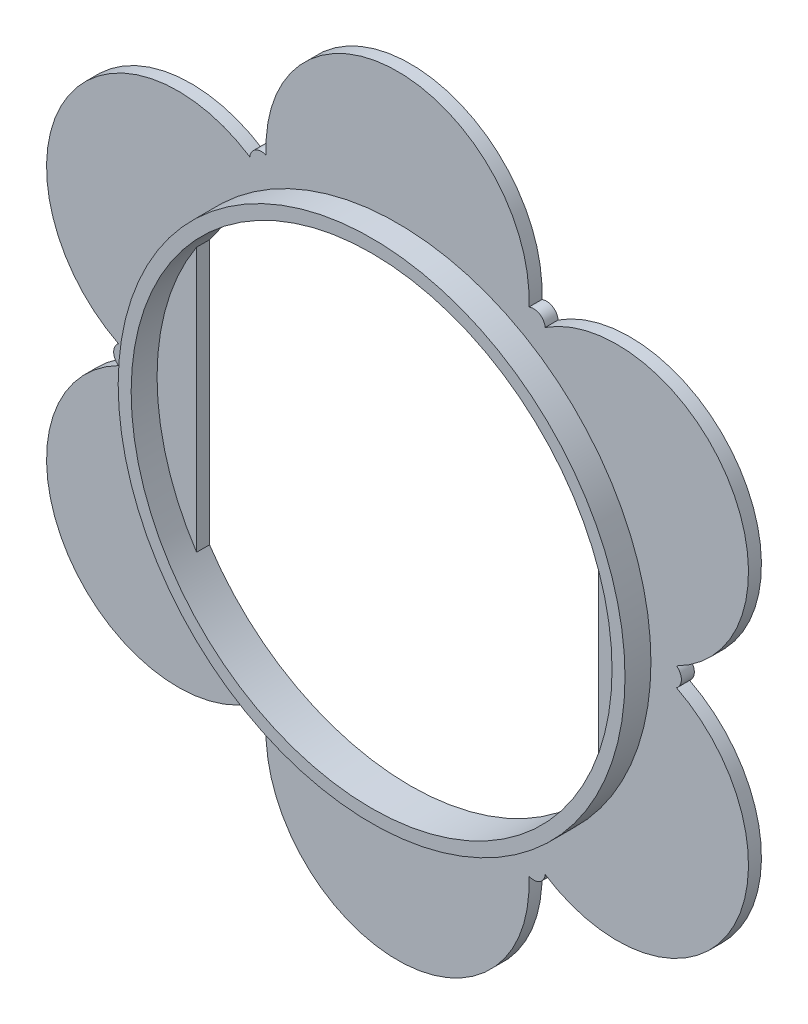
SolidWorks part; units mm, degrees
ref_plane "Front Plane" through (0, 0, 0) normal (0, 0, 1) x (1, 0, 0)
ref_plane "Top Plane" through (0, 0, 0) normal (0, 1, 0) x (1, 0, 0)
ref_plane "Right Plane" through (0, 0, 0) normal (1, 0, 0) x (0, 0, -1)
ref_plane "Plane1" through (0, 0, 1.8691) normal (0, 0, 1) x (1, 0, 0)
sketch "Sketch2" plane through (0, 0, 1.8691) normal (0, 0, 1) x (1, 0, 0)
  line L0 (-31, 20.3816) -> (-31, -20.3816)
  line L1 (0, -59.0896) -> (0, 59.3896) construction
  line L2 (31, 20.3816) -> (31, -20.3816)
  line L3 (0, 0) -> (0, 66.0605) construction
  circle A1 centre (-20.9977, 36.3691) radius 2 construction
  arc A3 (-20.474, -38.2993) -> (20.474, -38.2993) centre (0, -39.1) ccw construction
  arc A5 (-20.474, 38.2993) -> (-22.9311, 36.8806) centre (-20.9977, 36.3691) ccw construction
  arc A7 (20.474, 38.2993) -> (-20.474, 38.2993) centre (0, 39.1) ccw construction
  arc A9 (20.474, 38.2993) -> (-20.474, 38.2993) centre (0, 39.1) ccw construction
  arc A11 (-22.9311, 36.8806) -> (-43.4051, 1.4186) centre (-33.8616, 19.55) ccw construction
  arc A13 (-22.9311, 36.8806) -> (-43.4051, 1.4186) centre (-33.8616, 19.55) ccw construction
  arc A15 (21.4752, 38.3112) -> (20.474, 38.2993) centre (20.9977, 36.3691) ccw construction
  arc A17 (21.4752, 38.3112) -> (20.474, 38.2993) centre (20.9977, 36.3691) ccw construction
  arc A23 (22.4409, 37.7537) -> (21.4752, 38.3112) centre (20.9977, 36.3691) ccw construction
  arc A25 (22.4409, 37.7537) -> (21.4752, 38.3112) centre (20.9977, 36.3691) ccw construction
  arc A27 (-20.474, -38.2993) -> (20.474, -38.2993) centre (0, -39.1) ccw construction
  arc A28 (43.4051, 1.4186) -> (22.9311, 36.8806) centre (33.8616, 19.55) ccw construction
  arc A29 (43.4051, 1.4186) -> (22.9311, 36.8806) centre (33.8616, 19.55) ccw construction
  arc A30 (22.9311, 36.8806) -> (22.4409, 37.7537) centre (20.9977, 36.3691) ccw construction
  arc A31 (22.9311, 36.8806) -> (22.4409, 37.7537) centre (20.9977, 36.3691) ccw construction
  arc A32 (43.9161, 0.5576) -> (43.4051, 1.4186) centre (41.9954, 0) ccw construction
  arc A33 (43.9161, 0.5576) -> (43.4051, 1.4186) centre (41.9954, 0) ccw construction
  arc A34 (20.474, -38.2993) -> (21.4752, -38.3112) centre (20.9977, -36.3691) ccw construction
  arc A35 (22.9311, -36.8806) -> (43.4051, -1.4186) centre (33.8616, -19.55) ccw construction
  arc A36 (22.9311, -36.8806) -> (43.4051, -1.4186) centre (33.8616, -19.55) ccw construction
  arc A37 (43.4051, -1.4186) -> (43.9161, -0.5576) centre (41.9954, 0) ccw construction
  arc A38 (43.4051, -1.4186) -> (43.9161, -0.5576) centre (41.9954, 0) ccw construction
  arc A39 (43.9161, -0.5576) -> (43.9161, 0.5576) centre (41.9954, 0) ccw construction
  arc A40 (43.9161, -0.5576) -> (43.9161, 0.5576) centre (41.9954, 0) ccw construction
  arc A41 (20.474, -38.2993) -> (21.4752, -38.3112) centre (20.9977, -36.3691) ccw construction
  arc A42 (21.4752, -38.3112) -> (22.4409, -37.7537) centre (20.9977, -36.3691) ccw construction
  arc A43 (21.4752, -38.3112) -> (22.4409, -37.7537) centre (20.9977, -36.3691) ccw construction
  arc A44 (22.4409, -37.7537) -> (22.9311, -36.8806) centre (20.9977, -36.3691) ccw construction
  arc A45 (22.4409, -37.7537) -> (22.9311, -36.8806) centre (20.9977, -36.3691) ccw construction
  arc A46 (-21.4752, -38.3112) -> (-20.474, -38.2993) centre (-20.9977, -36.3691) ccw construction
  arc A47 (-21.4752, -38.3112) -> (-20.474, -38.2993) centre (-20.9977, -36.3691) ccw construction
  arc A48 (-22.4409, -37.7537) -> (-21.4752, -38.3112) centre (-20.9977, -36.3691) ccw construction
  arc A49 (-22.4409, -37.7537) -> (-21.4752, -38.3112) centre (-20.9977, -36.3691) ccw construction
  arc A50 (-22.9311, -36.8806) -> (-22.4409, -37.7537) centre (-20.9977, -36.3691) ccw construction
  arc A51 (-22.9311, -36.8806) -> (-22.4409, -37.7537) centre (-20.9977, -36.3691) ccw construction
  arc A52 (-43.4051, -1.4186) -> (-22.9311, -36.8806) centre (-33.8616, -19.55) ccw construction
  arc A53 (-43.4051, -1.4186) -> (-22.9311, -36.8806) centre (-33.8616, -19.55) ccw construction
  arc A54 (-43.9161, -0.5576) -> (-43.4051, -1.4186) centre (-41.9954, 0) ccw construction
  arc A55 (-43.9161, -0.5576) -> (-43.4051, -1.4186) centre (-41.9954, 0) ccw construction
  arc A56 (-43.9161, 0.5576) -> (-43.9161, -0.5576) centre (-41.9954, 0) ccw construction
  arc A57 (-43.9161, 0.5576) -> (-43.9161, -0.5576) centre (-41.9954, 0) ccw construction
  arc A58 (-43.4051, 1.4186) -> (-43.9161, 0.5576) centre (-41.9954, 0) ccw construction
  arc A59 (-43.4051, 1.4186) -> (-43.9161, 0.5576) centre (-41.9954, 0) ccw construction
  circle A60 centre (0, 0) radius 38.1 construction
  arc A61 (-31, -20.3816) -> (31, -20.3816) centre (0, 0) ccw
  arc A84 (-19.9637, -38.081) -> (19.9637, -38.081) centre (0, -39.1) ccw construction
  circle A85 centre (0, 0) radius 37.1 construction
  arc A86 (31, 20.3816) -> (-31, 20.3816) centre (0, 0) ccw
  arc A87 (-22.7884, 36.5516) -> (-43.0488, 1.4595) centre (-33.8616, 19.55) ccw
  arc A88 (-43.0488, 1.4595) -> (-43.724, 0.5018) centre (-41.9954, 0) ccw
  arc A89 (-43.724, 0.5018) -> (-43.724, -0.5018) centre (-41.9954, 0) ccw
  arc A90 (-43.724, -0.5018) -> (-43.0488, -1.4595) centre (-41.9954, 0) ccw
  arc A91 (-43.0488, -1.4595) -> (-22.7884, -36.5516) centre (-33.8616, -19.55) ccw
  arc A92 (-22.7884, -36.5516) -> (-22.2966, -37.6152) centre (-20.9977, -36.3691) ccw
  arc A93 (-22.2966, -37.6152) -> (-21.4274, -38.117) centre (-20.9977, -36.3691) ccw
  arc A94 (-21.4274, -38.117) -> (-20.2604, -38.0111) centre (-20.9977, -36.3691) ccw
  arc A95 (-20.2604, -38.0111) -> (20.2604, -38.0111) centre (0, -39.1) ccw
  arc A96 (20.2604, -38.0111) -> (21.4274, -38.117) centre (20.9977, -36.3691) ccw
  arc A97 (21.4274, -38.117) -> (22.2966, -37.6152) centre (20.9977, -36.3691) ccw
  arc A98 (22.2966, -37.6152) -> (22.7884, -36.5516) centre (20.9977, -36.3691) ccw
  arc A99 (22.7884, -36.5516) -> (43.0488, -1.4595) centre (33.8616, -19.55) ccw
  arc A100 (43.0488, -1.4595) -> (43.724, -0.5018) centre (41.9954, 0) ccw
  arc A101 (43.724, -0.5018) -> (43.724, 0.5018) centre (41.9954, 0) ccw
  arc A102 (43.724, 0.5018) -> (43.0488, 1.4595) centre (41.9954, 0) ccw
  arc A103 (43.0488, 1.4595) -> (22.7884, 36.5516) centre (33.8616, 19.55) ccw
  arc A104 (22.7884, 36.5516) -> (22.2966, 37.6152) centre (20.9977, 36.3691) ccw
  arc A105 (22.2966, 37.6152) -> (21.4274, 38.117) centre (20.9977, 36.3691) ccw
  arc A106 (21.4274, 38.117) -> (20.2604, 38.0111) centre (20.9977, 36.3691) ccw
  arc A107 (20.2604, 38.0111) -> (-20.2604, 38.0111) centre (0, 39.1) ccw
  arc A108 (-20.2604, 38.0111) -> (-22.7884, 36.5516) centre (-20.9977, 36.3691) ccw
  dimension "D4" = 76.2
  dimension "D3" = 31
  dimension "D1" = 1
  dimension "D2" = 0.2
extrude "Back Plate" add sketch "Sketch2" along normal blind 2
sketch "Sketch3" plane through (0, 0, 3.8691) normal (0, 0, 1) x (1, 0, 0)
  circle A0 centre (0, 0) radius 39.1
  circle A1 centre (0, 0) radius 37.1
  dimension "D1" = 78.2
  dimension "D2" = 2
extrude "Boss-Extrude2" add sketch "Sketch3" along normal blind 4
